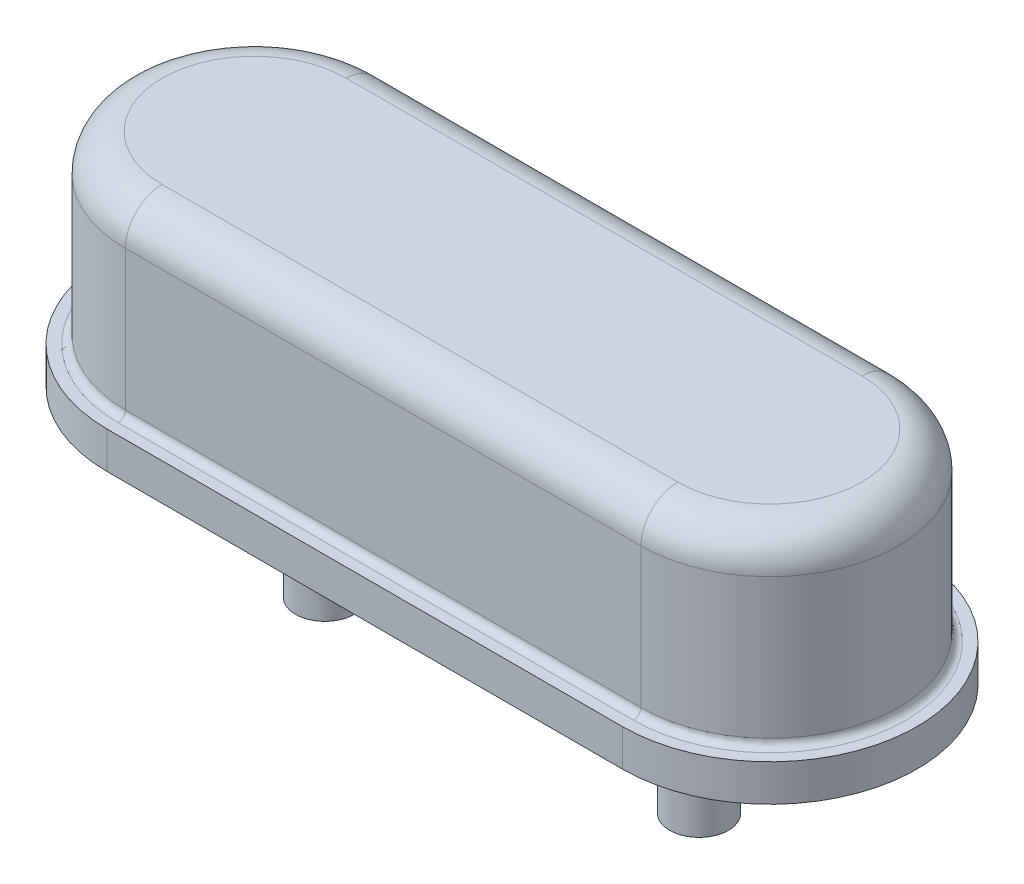
SolidWorks part; units mm, degrees
ref_plane "Front Plane" through (0, 0, 0) normal (0, 0, 1) x (1, 0, 0)
ref_plane "Top Plane" through (0, 0, 0) normal (0, 1, 0) x (1, 0, 0)
ref_plane "Right Plane" through (0, 0, 0) normal (1, 0, 0) x (0, 0, -1)
sketch "Sketch1" plane through (0, 0, 0) normal (0, 1, 0) x (1, 0, 0)
  line L0 (-3.5, 0) -> (3.5, 0) construction
  line L1 (-3.5, 2) -> (3.5, 2)
  line L2 (-3.5, -2) -> (3.5, -2)
  arc A0 (-3.5, 2) -> (-3.5, -2) centre (-3.5, 0) ccw
  arc A1 (3.5, -2) -> (3.5, 2) centre (3.5, 0) ccw
  point P2 (0, 0)
  dimension "D1" = 7
  dimension "D2" = 4
extrude "Boss-Extrude1" add sketch "Sketch1" along normal blind 3
sketch "Sketch2" plane through (0, 3, 0) normal (0, 1, 0) x (1, 0, 0)
  line L0 (-3.5, -1.75) -> (3.5, -1.75)
  line L1 (3.5, 1.75) -> (-3.5, 1.75)
  line L2 (-3.5, -2) -> (3.5, -2)
  line L3 (3.5, 2) -> (-3.5, 2)
  line L4 (-3.5, -2) -> (3.5, -2)
  line L5 (3.5, 2) -> (-3.5, 2)
  arc A0 (3.5, -1.75) -> (3.5, 1.75) centre (3.5, 0) ccw
  arc A1 (-3.5, 1.75) -> (-3.5, -1.75) centre (-3.5, 0) ccw
  arc A2 (-3.5, 2) -> (-3.5, -2) centre (-3.5, 0) ccw
  arc A3 (3.5, -2) -> (3.5, 2) centre (3.5, 0) ccw
  arc A4 (-3.5, 2) -> (-3.5, -2) centre (-3.5, 0) ccw
  arc A5 (3.5, -2) -> (3.5, 2) centre (3.5, 0) ccw
  dimension "D1" = 0
  dimension "D2" = 0.25
extrude "Cut-Extrude1" cut sketch "Sketch2" against normal blind 2.5
fillet "Fillet1" radius 0.5 4 edges at (-5.25, 3, 0) (0, 3, -1.75) (5.25, 3, 0) (0, 3, 1.75)
sketch "Sketch3" plane through (0, 0, 0) normal (0, -1, 0) x (1, 0, 0)
  circle A0 centre (-2.54, 0) radius 0.4
  circle A1 centre (2.54, 0) radius 0.4
  point P4 (0, 0)
  dimension "D1" = 0.8
  dimension "D2" = 0.8
  dimension "D3" = 2.54
  dimension "D4" = 2.54
extrude "Boss-Extrude2" add sketch "Sketch3" along normal blind 2
fillet "Fillet2" radius 0.1 4 edges at (-5.25, 0.5, 0) (0, 0.5, -1.75) (5.25, 0.5, 0) (0, 0.5, 1.75)
